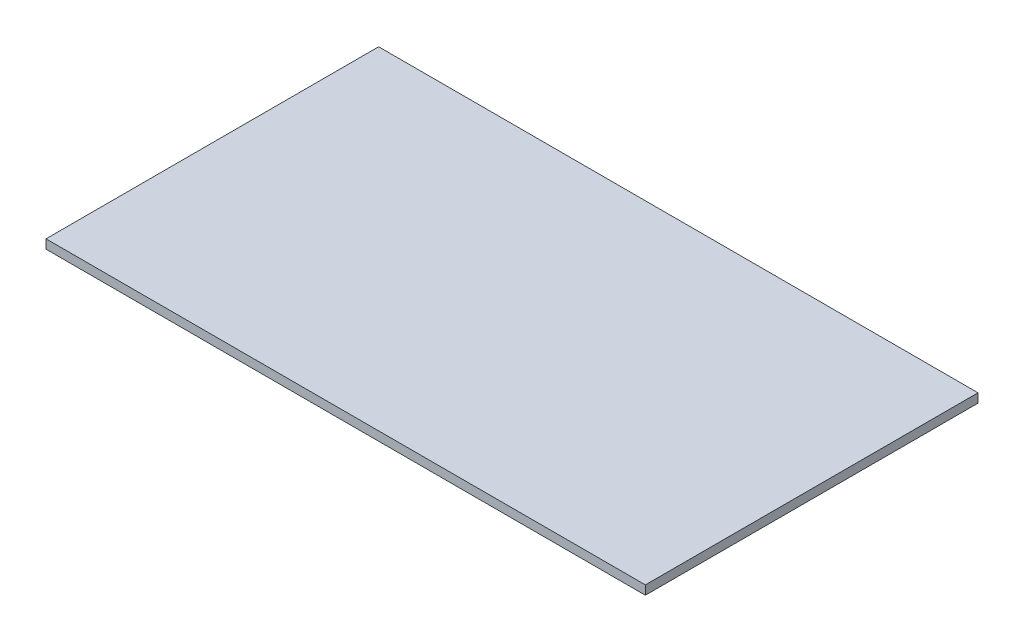
SolidWorks part; units mm, degrees
ref_plane "Front Plane" through (0, 0, 0) normal (0, 0, 1) x (1, 0, 0)
ref_plane "Top Plane" through (0, 0, 0) normal (0, 1, 0) x (1, 0, 0)
ref_plane "Right Plane" through (0, 0, 0) normal (1, 0, 0) x (0, 0, -1)
sketch "Sketch11" plane through (0, 0, 0) normal (0, 1, 0) x (1, 0, 0)
  line L1 (0, 0) -> (400, 0)
  line L2 (0, 0) -> (0, 222)
  line L3 (0, 222) -> (400, 222)
  line L4 (400, 0) -> (400, 222)
  dimension "D1" = 400
  dimension "D2" = 222
extrude "Boss-Extrude1" add sketch "Sketch11" along normal blind 6
